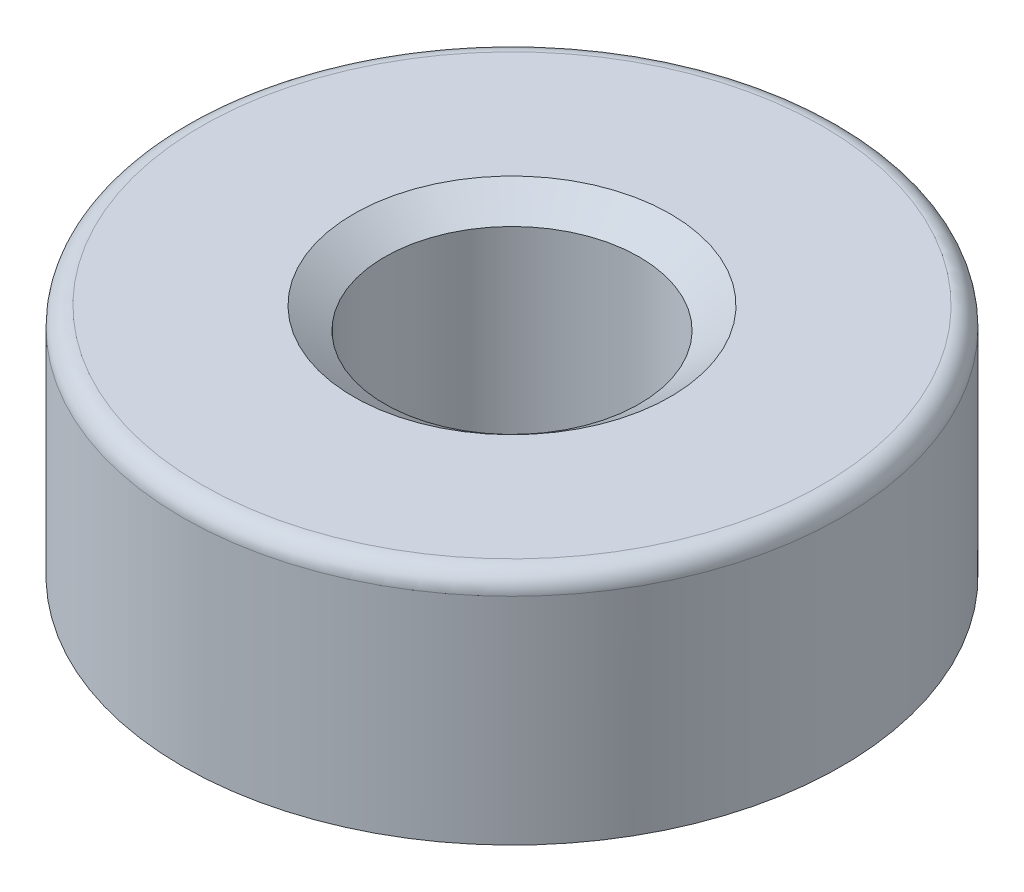
SolidWorks part; units mm, degrees
revolve "Body" add sketch "BodySke"
sketch "BodySke" plane through (0, 0, 0) normal (0, 0, 1) x (1, 0, 0)
  line L0 (4.0005, 0) -> (4.8675, 0)
  line L1 (6.604, 0) -> (6.604, 4.318)
  line L2 (6.223, 4.699) -> (2.5527, 4.699)
  line L3 (2.5527, 4.699) -> (2.5527, -1.2192)
  line L4 (2.5527, -1.2192) -> (4.0005, -1.2192)
  line L5 (4.0005, -1.2192) -> (4.0005, 0)
  line L6 (6.604, 0) -> (5.737, -0.6096)
  line L7 (1.016, 1.27) -> (3.6522, 1.27) construction
  line L8 (5.737, -0.6096) -> (4.8675, 0)
  line L9 (0, 0) -> (0, 15.24) construction
  arc A0 (6.604, 4.318) -> (6.223, 4.699) centre (6.223, 4.318) ccw
  point P14 (6.604, 4.699)
  dimension "D1" = 0.381
  dimension "E_dia" = 13.208
  dimension "C_dia" = 8.001
  dimension "A_ht" = 1.2192
  dimension "T_ht" = 4.699
  dimension "Thread_min" = 5.1054
  dimension "Advance" = 1.27
  dimension "Lug_minor_dia" = 9.7349
  dimension "Lug_tip_dia" = 11.4741
  dimension "Lug_ht" = 0.6096
cosmetic thread "ThreadCosmetic" [suppressed]
revolve "EndChamfer" cut sketch "EndChamferSke" angle 360 about L0
sketch "EndChamferSke" plane through (0, 0, 0) normal (0, 0, 1) x (1, 0, 0)
  line L0 (0, -2.54) -> (0, 7.62) construction
  line L1 (0, 0) -> (0, 15.24) construction
  line L2 (3.175, -1.4732) -> (3.175, -0.9652)
  line L3 (3.175, -0.9652) -> (2.5527, -0.5296)
  line L4 (2.5527, -0.5296) -> (2.5527, -1.4732)
  line L5 (2.5527, -1.4732) -> (3.175, -1.4732)
  line L6 (3.175, 4.699) -> (2.5527, 4.2634)
  line L8 (2.5527, 4.2634) -> (2.5527, 4.699)
  line L9 (3.175, 4.699) -> (2.5527, 4.699)
  line L10 (2.5527, 4.699) -> (-2.5527, 4.699) construction
  line L11 (-4.0005, -1.2192) -> (4.0005, -1.2192) construction
  dimension "D1" = 0.254
  dimension "Thread_nominal" = 6.35
  dimension "D2" = 34.99
  dimension "Thread_min" = 5.1054
  dimension "Inset" = 0.254
ref_plane "Plane1" through (0, 0, 0) normal (0, 0, 1) x (1, 0, 0)
ref_plane "Plane2" through (0, 0, 0) normal (0, 1, 0) x (1, 0, 0)
ref_plane "Plane3" through (0, 0, 0) normal (1, 0, 0) x (0, 0, -1)
ref_plane "Plane4" through (0, -0.5486, 0) normal (0, 1, 0) x (-1, 0, 0)
sketch "ThdSchSke" plane through (0, 0, 0) normal (0, 0, 1) x (1, 0, 0)
  line L0 (0, -5.08) -> (0, 7.62) construction
  line L1 (0, 0) -> (0, 15.24) construction
  line L2 (0, -0.9652) -> (3.175, -0.9652) construction
  line L4 (3.175, -0.9652) -> (2.5527, -0.5295)
  line L6 (3.175, -0.9652) -> (2.5527, -1.4009)
  line L7 (2.5527, -0.5295) -> (2.5527, -1.4009)
  line L8 (3.175, -0.9652) -> (-3.175, -0.9652) construction
  dimension "Thread_min" = 5.1054
  dimension "Thread_nominal" = 6.35
revolve "ThreadSchematic" [suppressed] cut sketch "ThdSchSke" angle 360 about L0
pattern_linear "ThdSchPat" [suppressed]
sketch "LugGapSke" plane through (0, 0, 0) normal (0, 1, 0) x (1, 0, 0)
  line L0 (-0.9258, -4.7786) -> (-1.8304, -6.3453)
  line L1 (4.6013, -1.5875) -> (6.4104, -1.5875)
  line L2 (0, 0) -> (-3.8626, -6.6901) construction
  line L3 (0, 0) -> (7.366, 0) construction
  arc A0 (-1.8304, -6.3453) -> (6.4104, -1.5875) centre (0, 0) ccw
  arc A1 (-0.9258, -4.7786) -> (4.6013, -1.5875) centre (0, 0) ccw
  circle A2 centre (0, 0) radius 4.8675 construction
  circle A3 centre (0, 0) radius 6.604 construction
extrude "LugGap" cut sketch "LugGapSke" against normal blind 6.35
pattern_circular "LugGapPat" count 3 every 120 about axis through (0, 0, 0) along (0, 1, 0) of "LugGap"
equation "' \"A_ht@BodySke\" = 0.048"
equation "' \"C_dia@BodySke\" = 0.315"
equation "' \"E_dia@BodySke\" = 0.52"
equation "' \"T_ht@BodySke\" = 0.185"
equation "' \"Advance@BodySke\" = 0.05"
equation "' \"Thread_min@BodySke\" = 0.201"
equation "' \"Thread_nominal@ThreadCosmetic\" = 0.25"
equation "\"Lug_ht@BodySke\" = \"A_ht@BodySke\" / 2"
equation "\"Lug_tip_dia@BodySke\" = \"C_dia@BodySke\" + (\"E_dia@BodySke\" - \"C_dia@BodySke\" ) * 0.667"
equation "\"Lug_minor_dia@BodySke\" = \"C_dia@BodySke\" + (\"E_dia@BodySke\" - \"C_dia@BodySke\" ) * 0.333"
equation "\"Lug_wid1@LugGapSke\" = \"Thread_nominal@ThreadCosmetic\" * 0.5"
equation "\"Lug_wid2@LugGapSke\" = \"Lug_wid1@LugGapSke\""
equation "\"Thread_nominal@EndChamferSke\" = \"Thread_nominal@ThreadCosmetic\""
equation "\"Thread_min@EndChamferSke\" = \"Thread_min@BodySke\""
equation "\"D2@EndChamferSke\" = \"Vee_angle@ThdSchSke\" / 2 - 0.01"
equation "\"Thread_nominal@ThdSchSke\" = \"Thread_nominal@ThreadCosmetic\""
equation "\"Thread_min@ThdSchSke\" = \"Thread_min@BodySke\""
equation "\"Num_threads@ThdSchPat\" = int(  ( \"A_ht@BodySke\" + \"T_ht@BodySke\" - \"Inset@EndChamferSke\" ) / \"Advance@BodySke\" + 0.999 )  + 1"
equation "\"Advance@ThdSchPat\" = (  \"A_ht@BodySke\" + \"T_ht@BodySke\" - \"Inset@EndChamferSke\"  ) /  (\"Num_threads@ThdSchPat\" - 1) 'relax it"
